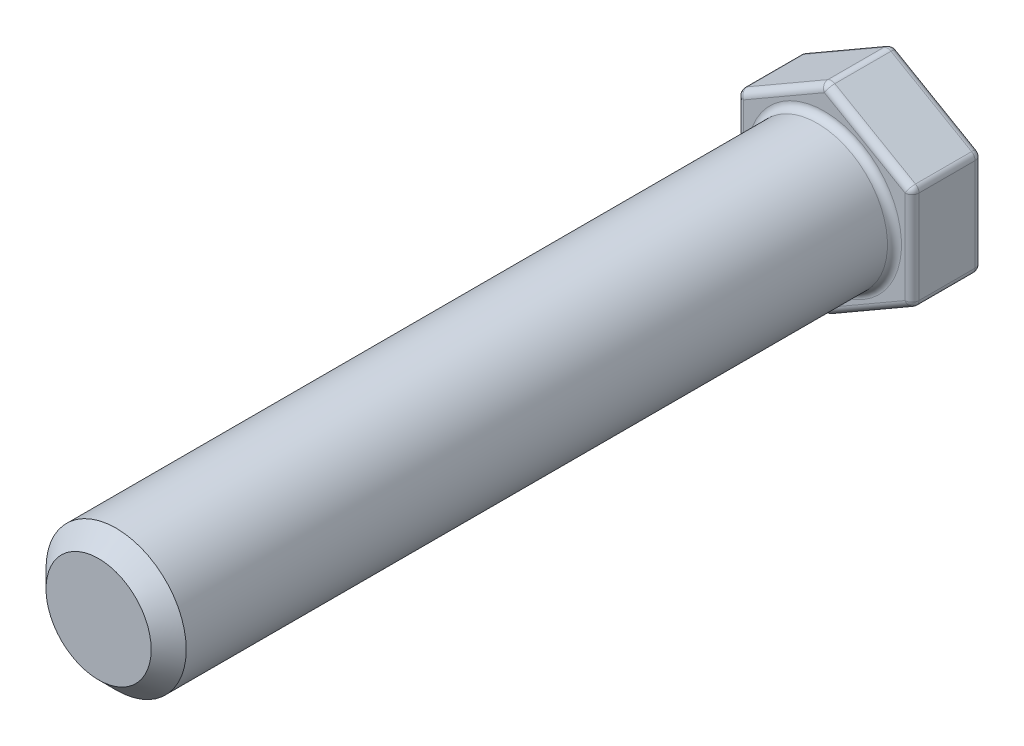
SolidWorks part; units mm, degrees
ref_plane "Front Plane" through (0, 0, 0) normal (0, 0, 1) x (1, 0, 0)
ref_plane "Top Plane" through (0, 0, 0) normal (0, 1, 0) x (1, 0, 0)
ref_plane "Right Plane" through (0, 0, 0) normal (1, 0, 0) x (0, 0, -1)
sketch "Sketch1" plane through (0, 0, 0) normal (0, 0, 1) x (1, 0, 0)
  circle A0 centre (0, 0) radius 2
  dimension "D1" = 4
extrude "Boss-Extrude1" add sketch "Sketch1" along normal blind 20.7
sketch "Sketch2" plane through (0, 0, 0) normal (0, 0, -1) x (-1, 0, 0)
  line L1 (-2.5, 1.4434) -> (-2.5, -1.4434)
  line L2 (-2.5, -1.4434) -> (0, -2.8868)
  line L3 (0, -2.8868) -> (2.5, -1.4434)
  line L4 (2.5, -1.4434) -> (2.5, 1.4434)
  line L5 (2.5, 1.4434) -> (0, 2.8868)
  line L6 (0, 2.8868) -> (-2.5, 1.4434)
  circle A0 centre (0, 0) radius 2.5 construction
  dimension "D1" = 5
extrude "Boss-Extrude2" add sketch "Sketch2" along normal blind 2
fillet "Fillet1" radius 0.2 13 edges at (2.5, 0, 0) (1.25, -2.1651, 0) (-1.25, -2.1651, 0) (-2.5, 0, 0) (-1.25, 2.1651, 0) (1.25, 2.1651, 0) (-2, 0, 0) (-1.25, 2.1651, -2) (-2.5, 0, -2) (-1.25, -2.1651, -2) (1.25, -2.1651, -2) (2.5, 0, -2) (1.25, 2.1651, -2)
fillet "Fillet2" radius 0.2 18 edges at (0, 2.8191, -1.9414) (0, 2.8191, -0.0586) (-2.4414, 1.4096, -1.9414) (-2.4414, 1.4096, -0.0586) (-2.4414, -1.4096, -1.9414) (-2.4414, -1.4096, -0.0586) (0, -2.8191, -1.9414) (0, -2.8191, -0.0586) (2.4414, -1.4096, -1.9414) (2.4414, -1.4096, -0.0586) (2.4414, 1.4096, -1.9414) (2.4414, 1.4096, -0.0586) (0, 2.8868, -1) (-2.5, 1.4434, -1) (-2.5, -1.4434, -1) (0, -2.8868, -1) (2.5, -1.4434, -1) (2.5, 1.4434, -1)
chamfer "Chamfer1" distance 0.5 angle 45 1 edges at (2, 0, 20.7)
